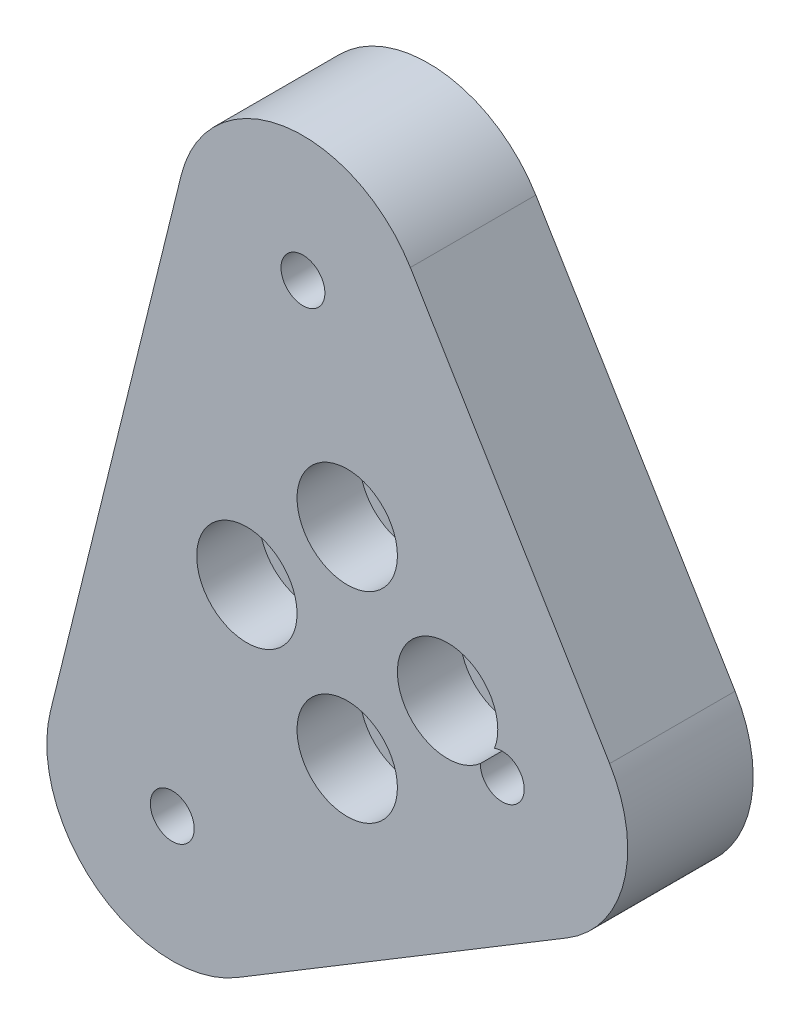
SolidWorks part; units mm, degrees
ref_plane "Front Plane" through (0, 0, 0) normal (0, 0, 1) x (1, 0, 0)
ref_plane "Top Plane" through (0, 0, 0) normal (0, 1, 0) x (1, 0, 0)
ref_plane "Right Plane" through (0, 0, 0) normal (1, 0, 0) x (0, 0, -1)
sketch "Sketch1" plane through (0, 0, 0) normal (0, 0, 1) x (1, 0, 0)
  line L0 (-13.9462, -18.9369) -> (-3.5289, 23.2519) construction
  line L1 (-3.5289, 23.2519) -> (12.3568, -3.0512) construction
  line L2 (12.3568, -3.0512) -> (-13.9462, -18.9369) construction
  line L3 (-23.6546, -16.5397) -> (-13.2373, 25.6491)
  line L4 (5.031, 28.4217) -> (20.9168, 2.1186)
  line L5 (17.5266, -11.6111) -> (-8.7764, -27.4969)
  line L6 (26.0866, -6.4413) -> (-29.442, -39.9779) construction
  line L7 (-29.442, -39.9779) -> (-7.45, 49.0873) construction
  line L8 (-7.45, 49.0873) -> (26.0866, -6.4413) construction
  circle A0 centre (0, 0) radius 9
  arc A3 (-23.6546, -16.5397) -> (-8.7764, -27.4969) centre (-13.9462, -18.9369) ccw
  arc A4 (5.031, 28.4217) -> (-13.2373, 25.6491) centre (-3.5289, 23.2519) ccw
  arc A5 (17.5266, -11.6111) -> (20.9168, 2.1186) centre (12.3568, -3.0512) ccw
  dimension "D1" = 18
  dimension "D2" = 45
  dimension "D3" = 45
  dimension "D4" = 10
extrude "Boss-Extrude1" add sketch "Sketch1" along normal blind 70
sketch "Sketch2" plane through (9.8226, -16.2639, 0) normal (0.517, -0.856, 0) x (0.856, 0.517, 0)
  line L0 (-21.7279, 70) -> (9, 70) construction
  circle A0 centre (0, 65) radius 2.5
  dimension "D1" = 5
  dimension "D2" = 5
extrude "Cut-Extrude1" cut sketch "Sketch2" against normal blind 5
sketch "Sketch3" plane through (7.2377, -11.984, 0) normal (0.517, -0.856, 0) x (0.856, 0.517, 0)
  circle A0 centre (0, 65) radius 1.75
  dimension "D1" = 3.5
extrude "Cut-Extrude2" cut sketch "Sketch3" against normal up to surface (5.1718 mm away)
pattern_circular "CirPattern1" count 3 over 360 about axis through (0, 0, 0) along (0, 0, 1) of "Cut-Extrude1", "Cut-Extrude2"
sketch "Sketch5" plane through (0, 0, 0) normal (0, 1, 0) x (1, 0, 0)
  line L0 (-24.5682, 0) -> (0, 0) construction
  line L2 (-24.5682, -30) -> (0, -30)
  line L3 (-24.5682, -5) -> (0, -5)
  line L4 (0, 0) -> (0, -30) construction
  line L6 (-24.5682, -30) -> (-24.5682, -5)
  line L7 (0, -30) -> (0, -5)
  dimension "D1" = 5
  dimension "D2" = 25
revolve "Cut-Revolve1" cut sketch "Sketch5" angle 360 about L4
sketch "Sketch6" plane through (0, 0, 0) normal (0, 0, -1) x (-1, 0, 0)
  circle A0 centre (0, 0) radius 9
extrude "Boss-Extrude2" add sketch "Sketch6" against normal up to surface (5 mm away) up to face at (9, 0, 5)
sketch "Sketch8" plane through (0, 0, 30) normal (0, 0, -1) x (-1, 0, 0)
  circle A0 centre (0, 0) radius 9 construction
  circle A1 centre (0, 0) radius 9
  circle A2 centre (0, 0) radius 5.0505
extrude "Boss-Extrude3" add sketch "Sketch8" against normal blind 3
sketch "Sketch9" plane through (0, 0, 0) normal (0, 0, -1) x (-1, 0, 0)
  circle A0 centre (0, 0) radius 8 construction
  circle A1 centre (0, 8) radius 1.875
  circle A2 centre (8, 0) radius 1.875
  circle A3 centre (0, -8) radius 1.875
  circle A4 centre (-8, 0) radius 1.875
  point P14 (0, 0)
  dimension "D1" = 16
  dimension "D2" = 3.75
  dimension "D3" = 4
extrude "Cut-Extrude3" cut sketch "Sketch9" against normal up to surface (5 mm away)
sketch "Sketch10" plane through (0, 0, 30) normal (0, 0, -1) x (-1, 0, 0)
  line L1 (13.2373, 25.6491) -> (23.6546, -16.5397) construction
  line L2 (8.7764, -27.4969) -> (-17.5266, -11.6111) construction
  line L3 (-20.9168, 2.1186) -> (-5.031, 28.4217) construction
  line L4 (13.2373, 25.6491) -> (23.6546, -16.5397)
  line L5 (8.7764, -27.4969) -> (-17.5266, -11.6111)
  line L6 (-20.9168, 2.1186) -> (-5.031, 28.4217)
  arc A0 (13.2373, 25.6491) -> (-5.031, 28.4217) centre (3.5289, 23.2519) ccw construction
  arc A1 (8.7764, -27.4969) -> (23.6546, -16.5397) centre (13.9462, -18.9369) ccw construction
  arc A2 (-20.9168, 2.1186) -> (-17.5266, -11.6111) centre (-12.3568, -3.0512) ccw construction
  arc A3 (13.2373, 25.6491) -> (-5.031, 28.4217) centre (3.5289, 23.2519) ccw
  arc A4 (8.7764, -27.4969) -> (23.6546, -16.5397) centre (13.9462, -18.9369) ccw
  arc A5 (-20.9168, 2.1186) -> (-17.5266, -11.6111) centre (-12.3568, -3.0512) ccw
sketch "Sketch11" plane through (0, 0, 0) normal (0, 0, -1) x (-1, 0, 0)
  circle A0 centre (0, 0) radius 4
  dimension "D1" = 8
extrude "Cut-Extrude4" cut sketch "Sketch11" against normal blind 3
sketch "Sketch12" plane through (0, 0, 0) normal (1, 0, 0) x (0, 0, -1)
  line L0 (-5, 35.5746) -> (-74.9237, 35.5746)
  line L1 (-74.9237, 35.5746) -> (-74.9237, -36.291)
  line L2 (-74.9237, -36.291) -> (-5, -36.291)
  line L3 (-5, -36.291) -> (-5, 35.5746)
extrude "Cut-Extrude5" cut sketch "Sketch12" against normal through all and the other way through all
sketch "Sketch13" plane through (0, 0, 5) normal (0, 0, 1) x (1, 0, 0)
  line L0 (-8.7764, -27.4969) -> (17.5266, -11.6111) construction
  line L1 (20.9168, 2.1186) -> (5.031, 28.4217) construction
  line L2 (-13.2373, 25.6491) -> (-23.6546, -16.5397) construction
  line L3 (-8.7764, -27.4969) -> (17.5266, -11.6111)
  line L4 (20.9168, 2.1186) -> (5.031, 28.4217)
  line L5 (-13.2373, 25.6491) -> (-23.6546, -16.5397)
  arc A0 (-23.6546, -16.5397) -> (-8.7764, -27.4969) centre (-13.9462, -18.9369) ccw construction
  arc A1 (17.5266, -11.6111) -> (20.9168, 2.1186) centre (12.3568, -3.0512) ccw construction
  arc A2 (5.031, 28.4217) -> (-13.2373, 25.6491) centre (-3.5289, 23.2519) ccw construction
  arc A3 (-23.6546, -16.5397) -> (-8.7764, -27.4969) centre (-13.9462, -18.9369) ccw
  arc A4 (17.5266, -11.6111) -> (20.9168, 2.1186) centre (12.3568, -3.0512) ccw
  arc A5 (5.031, 28.4217) -> (-13.2373, 25.6491) centre (-3.5289, 23.2519) ccw
  circle A6 centre (-8, 0) radius 4
  circle A7 centre (0, 8) radius 4
  circle A8 centre (8, 0) radius 4
  circle A9 centre (0, -8) radius 4
  dimension "D1" = 8
extrude "Boss-Extrude5" add sketch "Sketch13" along normal blind 5
sketch "Sketch14" plane through (0, 0, 0) normal (0, 0, -1) x (-1, 0, 0)
  circle A0 centre (3.5289, 23.2519) radius 1.75
  circle A1 centre (-12.3568, -3.0512) radius 1.75
  circle A2 centre (13.9462, -18.9369) radius 1.75
  dimension "D1" = 3.5
extrude "Cut-Extrude6" cut sketch "Sketch14" against normal through all
equation "\"fuse_diam\"= 0.07"
equation "\"fuse_rad\"= 0.035"
equation "\"battery_length\"= 0.076"
equation "\"battery_width\"= 0.034"
equation "\"battery_height\"= 0.051"
equation "\"bat_bay_length\"= 0.096"
equation "\"wing_shelf\"= 0.0175"
equation "\"shell\"= 0.002"
equation "\"chord_length\"= 0.09"
equation "\"tail_length\"= 0.26598000000000005"
equation "\"tail_diam\"= 0.035"
equation "\"connector\"= 0.06649500000000001"
